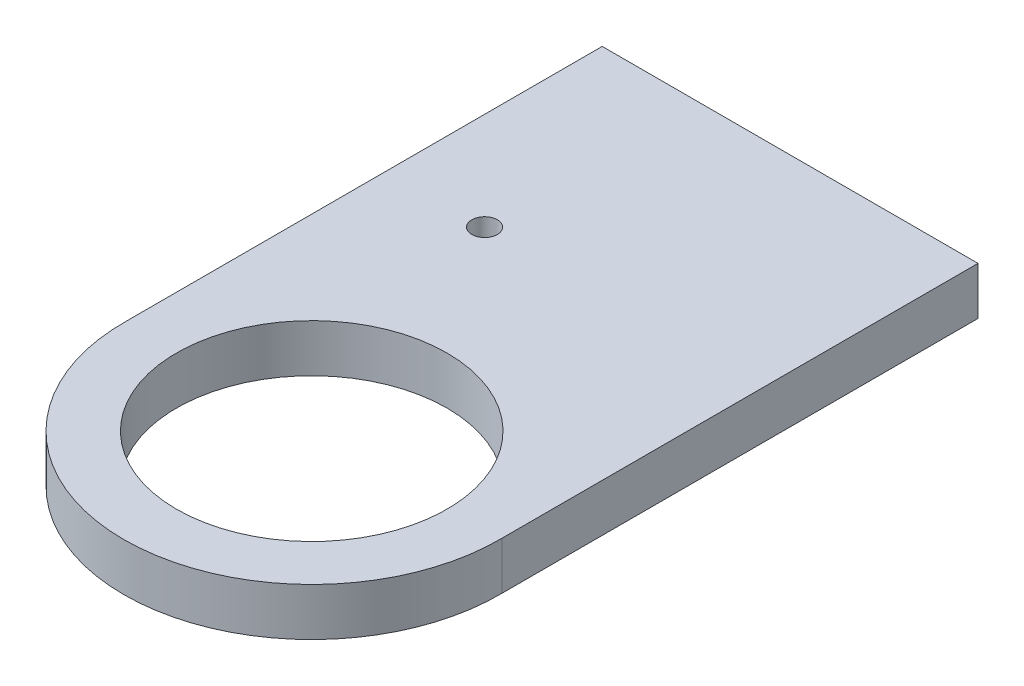
SolidWorks part; units mm, degrees
material "Aleación 6061"
ref_plane "Alzado" through (0, 0, 0) normal (0, 0, 1) x (1, 0, 0)
ref_plane "Planta" through (0, 0, 0) normal (0, 1, 0) x (1, 0, 0)
ref_plane "Vista lateral" through (0, 0, 0) normal (1, 0, 0) x (0, 0, -1)
sketch "Sk_Pared" plane through (0, 0, 0) normal (0, 1, 0) x (1, 0, 0)
  line L1 (-25, -489.65) -> (25, -489.65)
  line L2 (-25, -489.65) -> (-25, -426.35)
  line L3 (-25, -426.35) -> (25, -426.35)
  line L4 (25, -489.65) -> (25, -426.35)
  line L5 (-25, -489.65) -> (25, -426.35) construction
  line L6 (-25, -426.35) -> (25, -489.65) construction
  point P0 (0, -458)
  dimension "D1" = 50
  dimension "D2" = 63.3
  dimension "D3" = 458
extrude "Pared" add sketch "Sk_Pared" along normal blind 6.35 from offset 21.5
sketch "Sk_Cabeza" plane through (0, 0, 0) normal (0, 1, 0) x (1, 0, 0)
  circle A0 centre (0, -490) radius 25
  dimension "D1" = 50
  dimension "D2" = 490
extrude "Cabeza" add sketch "Sk_Cabeza" along normal blind 6.35 from offset 21.5
sketch "Sk_Paso_cubo_J5" plane through (0, 0, 0) normal (0, 1, 0) x (1, 0, 0)
  circle A0 centre (0, -490) radius 18
  dimension "D1" = 36
  dimension "D2" = 490
extrude "Paso_cubo_J5" cut sketch "Sk_Paso_cubo_J5" along normal blind 6.35 from offset 21.5
sketch "Sk_Pasantes_M4_angulos" plane through (0, 0, 0) normal (0, 1, 0) x (1, 0, 0)
  circle A0 centre (-20, -437.11) radius 2.25
  circle A1 centre (20, -437.11) radius 2.25
  dimension "D1" = 4.5
  dimension "D4" = 4.5
  dimension "D2" = 20
  dimension "D3" = 437.11
  dimension "D5" = 20
  dimension "D6" = 437.11
sketch "Sk_Pasante_M3_cincho" plane through (0, 0, 0) normal (0, 1, 0) x (1, 0, 0)
  circle A0 centre (-12, -455) radius 1.7
  dimension "D1" = 3.4
  dimension "D2" = 12
  dimension "D3" = 455
extrude "Pasante_M3_cincho" cut sketch "Sk_Pasante_M3_cincho" along normal blind 6.35 from offset 21.5
sketch "Sk_Rosca_M3_desde_abajo" plane through (0, 0, 426.35) normal (0, 0, -1) x (-1, 0, 0)
  circle A0 centre (15, 24.675) radius 1.25
  circle A1 centre (-15, 24.675) radius 1.25
extrude "Rosca_M3_desde_abajo" cut sketch "Sk_Rosca_M3_desde_abajo" against normal blind 9
